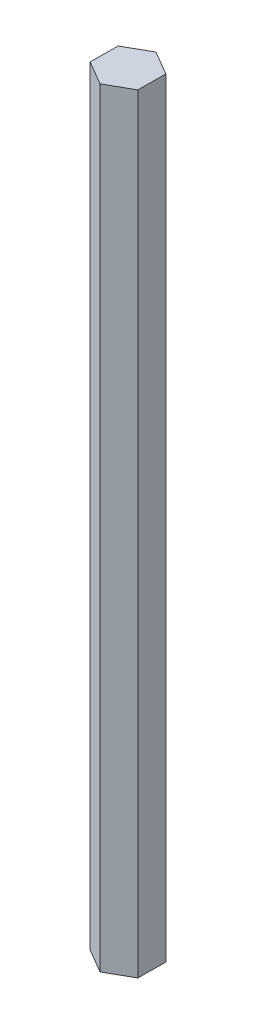
SolidWorks part; units mm, degrees
ref_plane "Front Plane" through (0, 0, 0) normal (0, 0, 1) x (1, 0, 0)
ref_plane "Top Plane" through (0, 0, 0) normal (0, 1, 0) x (1, 0, 0)
ref_plane "Right Plane" through (0, 0, 0) normal (1, 0, 0) x (0, 0, -1)
sketch "Sketch1" plane through (0, 0, 0) normal (0, 1, 0) x (1, 0, 0)
  line L1 (-6.3778, -3.6176) -> (-0.0559, -7.3321)
  line L2 (-0.0559, -7.3321) -> (6.3219, -3.7145)
  line L3 (6.3219, -3.7145) -> (6.3778, 3.6176)
  line L4 (6.3778, 3.6176) -> (0.0559, 7.3321)
  line L5 (0.0559, 7.3321) -> (-6.3219, 3.7145)
  line L6 (-6.3219, 3.7145) -> (-6.3778, -3.6176)
  circle A0 centre (0, 0) radius 6.35 construction
  dimension "D1" = 12.7
extrude "Boss-Extrude1" add sketch "Sketch1" along normal blind 203.2
